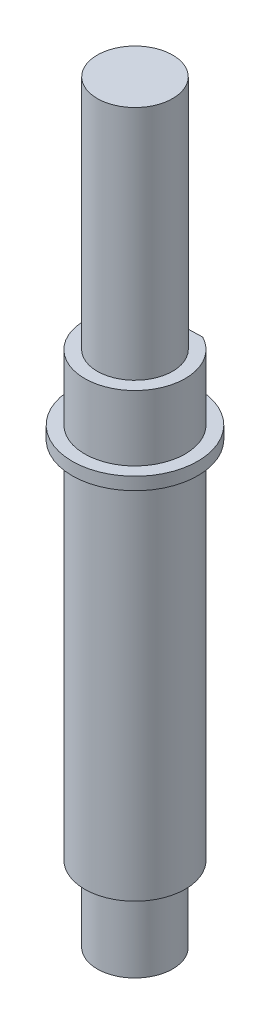
SolidWorks part; units mm, degrees
ref_plane "前视基准面" through (0, 0, 0) normal (0, 0, 1) x (1, 0, 0)
ref_plane "上视基准面" through (0, 0, 0) normal (0, 1, 0) x (1, 0, 0)
ref_plane "右视基准面" through (0, 0, 0) normal (1, 0, 0) x (0, 0, -1)
sketch "草图1" plane through (0, 0, 0) normal (0, 1, 0) x (1, 0, 0)
  circle A0 centre (0, 0) radius 1.5
extrude "凸台-拉伸1" add sketch "草图1" along normal blind 30
ref_plane "基准面1" through (0, 18, 0) normal (0, -1, 0) x (-1, 0, 0)
sketch "草图2" plane through (0, 18, 0) normal (0, -1, 0) x (-1, 0, 0)
  circle A0 centre (0, 0) radius 1.5
  circle A1 centre (0, 0) radius 2
extrude "凸台-拉伸2" add sketch "草图2" along normal blind 15
sketch "草图3" plane through (0, 18, 0) normal (0, 1, 0) x (1, 0, 0)
  line L1 (0.9163, 1.7778) -> (-1.0222, 1.719)
  circle A0 centre (0, 0) radius 1.5
  arc A1 (-1.0222, 1.719) -> (0.9163, 1.7778) centre (0, 0) ccw
extrude "凸台-拉伸3" add sketch "草图3" along normal blind 2.6
sketch "草图4" plane through (0, 18, 0) normal (0, 1, 0) x (1, 0, 0)
  circle A0 centre (0, 0) radius 2
  circle A1 centre (0, 0) radius 2.5
extrude "凸台-拉伸4" add sketch "草图4" against normal blind 0.5
